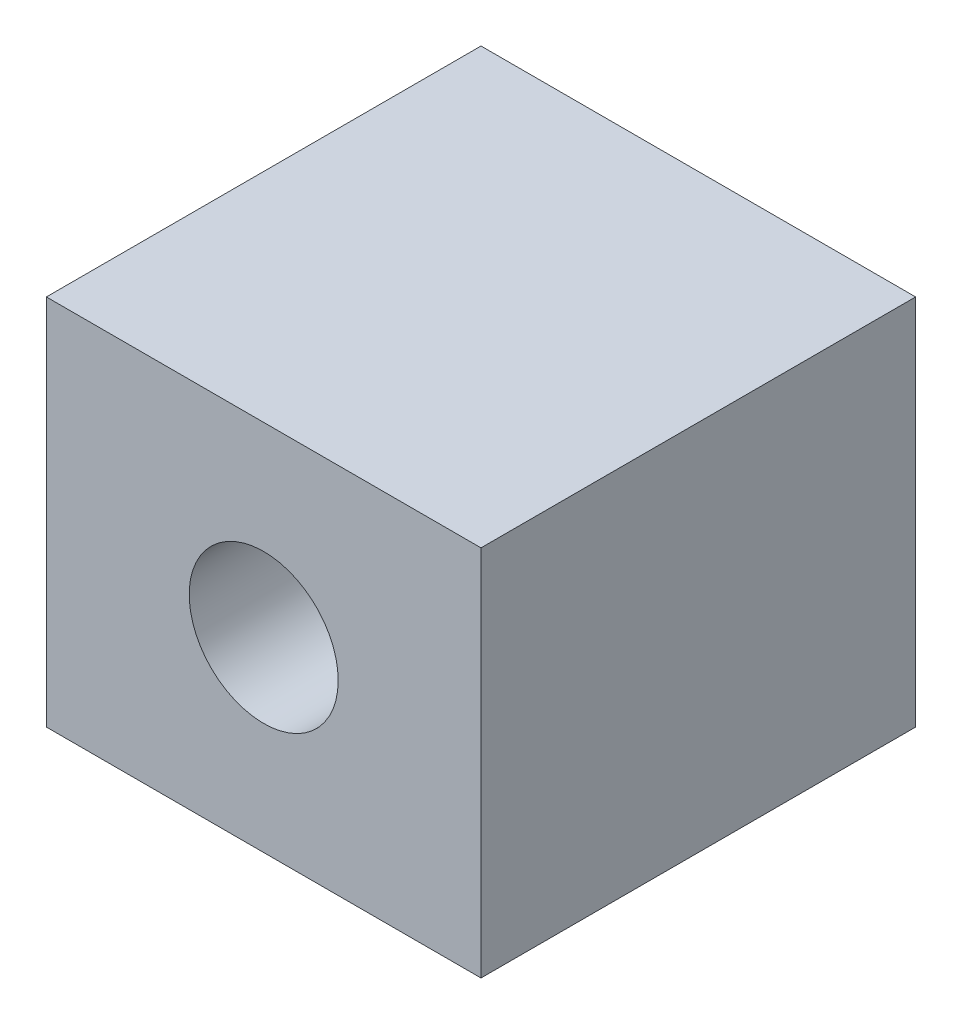
SolidWorks part; units mm, degrees
ref_plane "Front Plane" through (0, 0, 0) normal (0, 0, 1) x (1, 0, 0)
ref_plane "Top Plane" through (0, 0, 0) normal (0, 1, 0) x (1, 0, 0)
ref_plane "Right Plane" through (0, 0, 0) normal (1, 0, 0) x (0, 0, -1)
sketch "Sketch1" plane through (0, 0, 0) normal (0, 0, 1) x (1, 0, 0)
  line L1 (-17.5, -15) -> (17.5, -15)
  line L2 (-17.5, -15) -> (-17.5, 15)
  line L3 (-17.5, 15) -> (17.5, 15)
  line L4 (17.5, -15) -> (17.5, 15)
  line L5 (-17.5, -15) -> (17.5, 15) construction
  line L6 (-17.5, 15) -> (17.5, -15) construction
  circle A0 centre (0, 0) radius 6
  point P0 (0, 0)
  dimension "D1" = 12
  dimension "D2" = 30
  dimension "D3" = 35
extrude "Boss-Extrude1" add sketch "Sketch1" along normal blind 35
